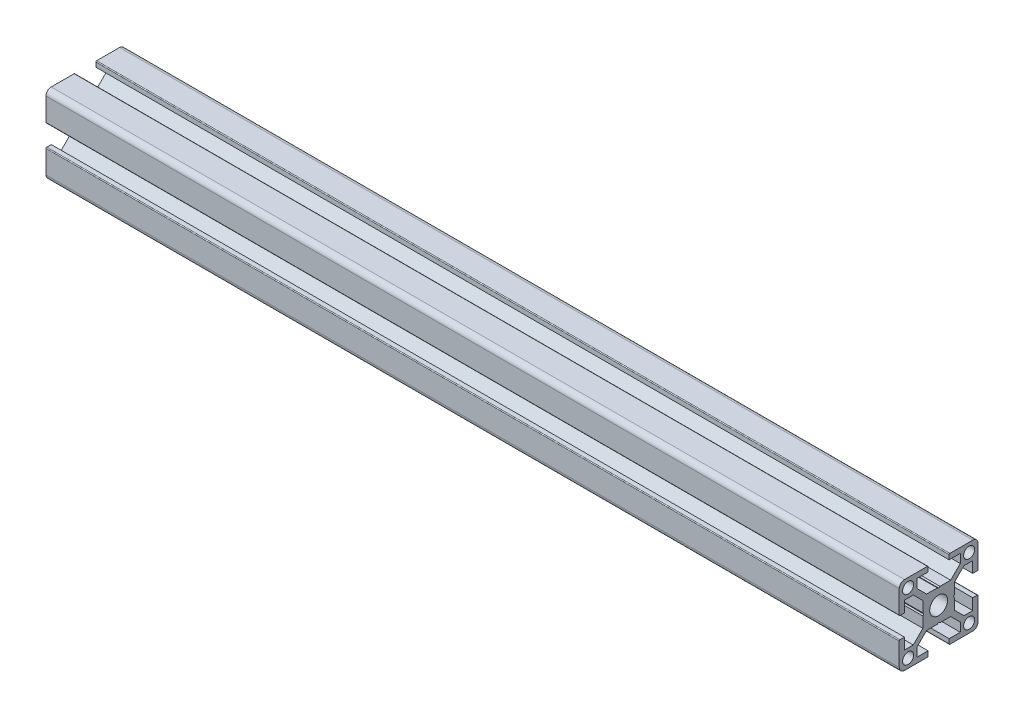
SolidWorks part; units mm, degrees
ref_plane "Front Plane" through (0, 0, 0) normal (0, 0, 1) x (1, 0, 0)
ref_plane "Top Plane" through (0, 0, 0) normal (0, 1, 0) x (1, 0, 0)
ref_plane "Right Plane" through (0, 0, 0) normal (1, 0, 0) x (0, 0, -1)
sketch "Sketch1" plane through (0, 0, 0) normal (0, 0, 1) x (1, 0, 0)
  line L0 (0, 0) -> (325, 0)
  dimension "D1" = 325
other "30xs6 30X30S6(1)"
ref_plane "Plane1" through (0, 0, 0) normal (1, 0, 0) x (0, 1, 0)
sketch "草图1" plane through (0, 0, 0) normal (1, 0, 0) x (0, 1, 0)
  line L0 (-14.7, 4) -> (-13, 4)
  line L1 (-13, 4) -> (-13, 8.25)
  line L2 (-13, 8.25) -> (-9.6642, 8.25)
  line L3 (-9.6642, 8.25) -> (-6, 4.5858)
  line L4 (-6, 4.5858) -> (-6, 0.5196)
  line L5 (-6, 0.5196) -> (-5.7, 0)
  line L6 (-5.7, 0) -> (-6, -0.5196)
  line L7 (-6, -0.5196) -> (-6, -4.5858)
  line L8 (-6, -4.5858) -> (-9.6642, -8.25)
  line L9 (-9.6642, -8.25) -> (-13, -8.25)
  line L10 (-13, -8.25) -> (-13, -4)
  line L11 (-13, -4) -> (-14.7, -4)
  line L12 (-15, -4.3) -> (-15, -13)
  line L13 (-13, -15) -> (-4.3, -15)
  line L14 (-4, -14.7) -> (-4, -13)
  line L15 (-4, -13) -> (-8.25, -13)
  line L16 (-8.25, -13) -> (-8.25, -9.6642)
  line L17 (-8.25, -9.6642) -> (-4.5858, -6)
  line L18 (-4.5858, -6) -> (-0.5196, -6)
  line L19 (-0.5196, -6) -> (0, -5.7)
  line L20 (0, -5.7) -> (0.5196, -6)
  line L21 (0.5196, -6) -> (4.5858, -6)
  line L22 (4.5858, -6) -> (8.25, -9.6642)
  line L23 (8.25, -9.6642) -> (8.25, -13)
  line L24 (8.25, -13) -> (4, -13)
  line L25 (4, -13) -> (4, -14.7)
  line L26 (4.3, -15) -> (13, -15)
  line L27 (15, -13) -> (15, -4.3)
  line L28 (14.7, -4) -> (13, -4)
  line L29 (13, -4) -> (13, -8.25)
  line L30 (13, -8.25) -> (9.6642, -8.25)
  line L31 (9.6642, -8.25) -> (6, -4.5858)
  line L32 (6, -4.5858) -> (6, -0.5196)
  line L33 (6, -0.5196) -> (5.7, 0)
  line L34 (5.7, 0) -> (6, 0.5196)
  line L35 (6, 0.5196) -> (6, 4.5858)
  line L36 (6, 4.5858) -> (9.6642, 8.25)
  line L37 (9.6642, 8.25) -> (13, 8.25)
  line L38 (13, 8.25) -> (13, 4)
  line L39 (13, 4) -> (14.7, 4)
  line L40 (15, 4.3) -> (15, 13)
  line L41 (13, 15) -> (4.3, 15)
  line L42 (4, 14.7) -> (4, 13)
  line L43 (4, 13) -> (8.25, 13)
  line L44 (8.25, 13) -> (8.25, 9.6642)
  line L45 (8.25, 9.6642) -> (4.5858, 6)
  line L46 (4.5858, 6) -> (0.5196, 6)
  line L47 (0.5196, 6) -> (0, 5.7)
  line L48 (0, 5.7) -> (-0.5196, 6)
  line L49 (-0.5196, 6) -> (-4.5858, 6)
  line L50 (-4.5858, 6) -> (-8.25, 9.6642)
  line L51 (-8.25, 9.6642) -> (-8.25, 13)
  line L52 (-8.25, 13) -> (-4, 13)
  line L53 (-4, 13) -> (-4, 14.7)
  line L54 (-4.3, 15) -> (-13, 15)
  line L55 (-15, 13) -> (-15, 4.3)
  arc A0 (-15, 4.3) -> (-14.7, 4) centre (-14.7, 4.3) ccw
  arc A1 (-14.7, -4) -> (-15, -4.3) centre (-14.7, -4.3) ccw
  arc A2 (-15, -13) -> (-13, -15) centre (-13, -13) ccw
  arc A3 (-4.3, -15) -> (-4, -14.7) centre (-4.3, -14.7) ccw
  arc A4 (4, -14.7) -> (4.3, -15) centre (4.3, -14.7) ccw
  arc A5 (13, -15) -> (15, -13) centre (13, -13) ccw
  arc A6 (15, -4.3) -> (14.7, -4) centre (14.7, -4.3) ccw
  arc A7 (14.7, 4) -> (15, 4.3) centre (14.7, 4.3) ccw
  arc A8 (15, 13) -> (13, 15) centre (13, 13) ccw
  arc A9 (4.3, 15) -> (4, 14.7) centre (4.3, 14.7) ccw
  arc A10 (-4, 14.7) -> (-4.3, 15) centre (-4.3, 14.7) ccw
  arc A11 (-13, 15) -> (-15, 13) centre (-13, 13) ccw
  circle A12 centre (11.625, 11.625) radius 2.1
  circle A13 centre (11.625, -11.625) radius 2.1
  circle A14 centre (0, 0) radius 3.4
  circle A15 centre (-11.625, -11.625) radius 2.1
  circle A16 centre (-11.625, 11.625) radius 2.1
  point P90 (-15, 15)
  point P91 (-0.2598, 14.9121)
  point P92 (15, 15)
  point P93 (15, 0)
  point P94 (15, -15)
  point P95 (0.2598, -15)
  point P96 (-15, -15)
  point P97 (-15, 0)
  point P98 (0, 0)
